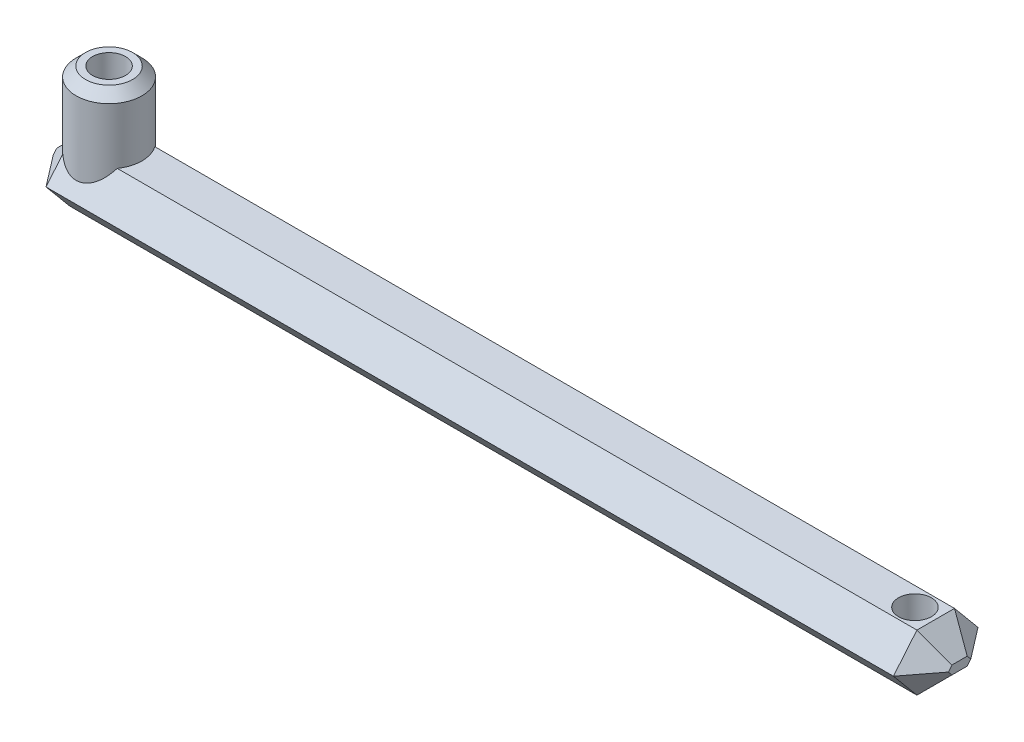
SolidWorks part; units mm, degrees
material "Plain Carbon Steel"
ref_plane "Front Plane" through (0, 0, 0) normal (0, 0, 1) x (1, 0, 0)
ref_plane "Top Plane" through (0, 0, 0) normal (0, 1, 0) x (1, 0, 0)
ref_plane "Right Plane" through (0, 0, 0) normal (1, 0, 0) x (0, 0, -1)
sketch "Sketch1" plane through (0, 0, 0) normal (1, 0, 0) x (0, 0, -1)
  line L0 (-2, -3) -> (-4.5, 0)
  line L1 (-2, -3) -> (2, -3)
  line L3 (-2, 3) -> (2, 3)
  line L5 (-2, -3) -> (2, 3) construction
  line L6 (-2, 3) -> (2, -3) construction
  line L7 (-4.5, 0) -> (-2, 3)
  line L8 (2, 3) -> (4.5, 0)
  line L9 (4.5, 0) -> (2, -3)
  point P0 (0, 0)
  dimension "D1" = 9
  dimension "D2" = 4
  dimension "D3" = 6
extrude "Boss-Extrude1" add sketch "Sketch1" along normal mid plane 95.25 contours L8 L9 L1 L0 L7 L3
sketch "Sketch2" plane through (0, -3, 0) normal (0, -1, 0) x (1, 0, 0)
  line L0 (47.625, 2) -> (47.625, -2) construction
  circle A0 centre (42.875, 0) radius 1.75
  point P2 (47.625, 0)
  dimension "D1" = 3.5
  dimension "D2" = 3
extrude "Cut-Extrude1" cut sketch "Sketch2" against normal up to surface (6 mm away) up to face at (0, 3, 0)
chamfer "Chamfer1" distance 2.54 angle 45 6 edges at (47.625, 1.5, -3.25) (47.625, -1.5, -3.25) (47.625, -3, 0) (47.625, -1.5, 3.25) (47.625, 1.5, 3.25) (47.625, 3, 0)
mirror "Mirror4" about plane through (0, 0, 0) normal (1, 0, 0) of "Cut-Extrude1"
chamfer "Chamfer2" distance 2.54 angle 45 6 edges at (-47.625, 1.5, 3.25) (-47.625, -1.5, 3.25) (-47.625, -3, 0) (-47.625, -1.5, -3.25) (-47.625, 1.5, -3.25) (-47.625, 3, 0)
sketch "Sketch3" plane through (0, 3, 0) normal (0, 1, 0) x (1, 0, 0)
  circle A0 centre (-42.875, 0) radius 3.5
  circle A1 centre (-42.875, 0) radius 1.75 construction
  circle A2 centre (-42.875, 0) radius 1.75
  dimension "D1" = 7
extrude "Boss-Extrude2" add sketch "Sketch3" along normal blind 7 and the other way up to next
chamfer "Chamfer3" distance 1 angle 45 1 edges at (-42.875, 10, 3.5)
